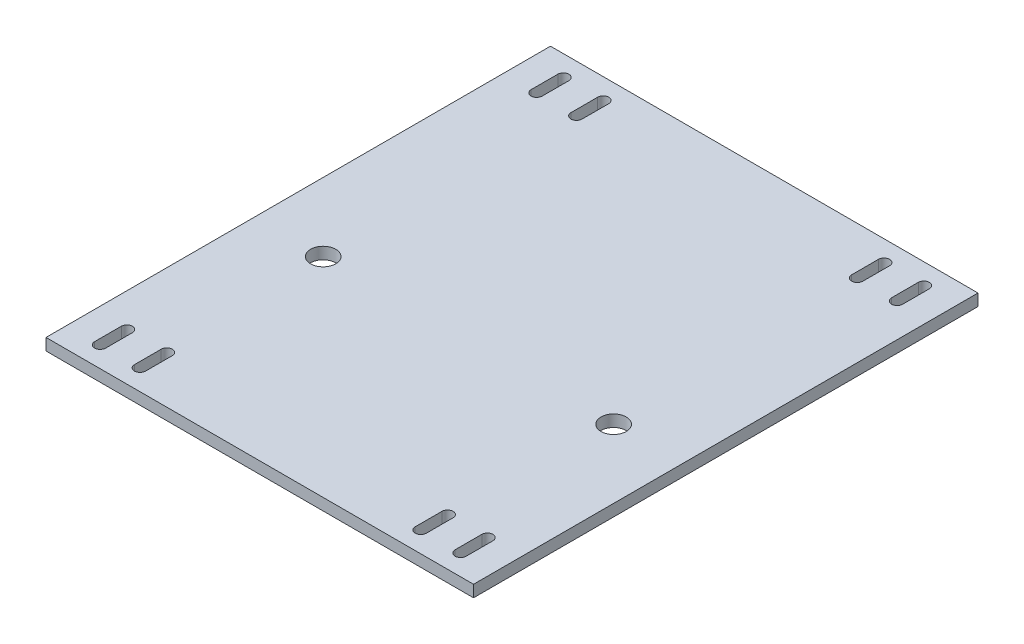
SolidWorks part; units mm, degrees
ref_plane "Front Plane" through (0, 0, 0) normal (0, 0, 1) x (1, 0, 0)
ref_plane "Top Plane" through (0, 0, 0) normal (0, 1, 0) x (1, 0, 0)
ref_plane "Right Plane" through (0, 0, 0) normal (1, 0, 0) x (0, 0, -1)
sketch "Sketch1" plane through (0, 0, 0) normal (0, 1, 0) x (1, 0, 0)
  line L1 (-76.2, -119.888) -> (76.2, -119.888)
  line L2 (-76.2, -119.888) -> (-76.2, 119.888)
  line L3 (-76.2, 119.888) -> (76.2, 119.888)
  line L4 (76.2, -119.888) -> (76.2, 119.888)
  line L5 (-76.2, -119.888) -> (76.2, 119.888) construction
  line L6 (-76.2, 119.888) -> (76.2, -119.888) construction
  point P0 (0, 0)
  dimension "D1" = 152.4
  dimension "D2" = 239.776
extrude "Boss-Extrude1" add sketch "Sketch1" along normal blind 5.588
sketch "Sketch2" plane through (0, 5.588, 0) normal (0, 1, 0) x (1, 0, 0)
  line L0 (0, 0) -> (44.9308, 9.86) construction
  line L1 (44.9308, 9.86) -> (44.9308, 0) construction
  line L2 (39.9308, -24) -> (49.9308, -24) construction
  line L3 (39.9308, -24) -> (39.9308, 24) construction
  line L4 (39.9308, 24) -> (49.9308, 24) construction
  line L5 (49.9308, -24) -> (49.9308, 24) construction
  line L6 (39.9308, -24) -> (49.9308, 24) construction
  line L7 (39.9308, 24) -> (49.9308, -24) construction
  line L8 (0, 26.208) -> (0, -26.6297) construction
  line L9 (44.9308, 0) -> (76.2, 0) construction
  line L10 (76.2, -119.888) -> (76.2, 119.888) construction
  line L11 (-33.9308, 21) -> (-55.9308, 21)
  line L12 (33.9308, -21) -> (55.9308, -21)
  line L13 (33.9308, -21) -> (33.9308, 21)
  line L14 (33.9308, 21) -> (55.9308, 21)
  line L15 (55.9308, -21) -> (55.9308, 21)
  line L16 (33.9308, -21) -> (55.9308, 21) construction
  line L17 (33.9308, 21) -> (55.9308, -21) construction
  line L18 (-55.9308, -21) -> (-55.9308, 21)
  line L19 (-33.9308, -21) -> (-55.9308, -21)
  line L20 (-33.9308, -21) -> (-33.9308, 21)
  circle A0 centre (0, 0) radius 40 construction
  circle A1 centre (44.9308, 9.86) radius 6 construction
  circle A2 centre (39.9308, 24) radius 2.25
  circle A3 centre (49.9308, 24) radius 2.25
  circle A4 centre (39.9308, -24) radius 2.25
  circle A5 centre (49.9308, -24) radius 2.25
  circle A6 centre (-49.9308, -24) radius 2.25
  circle A7 centre (-39.9308, -24) radius 2.25
  circle A8 centre (-49.9308, 24) radius 2.25
  circle A9 centre (-39.9308, 24) radius 2.25
  point P5 (44.9308, 0)
  dimension "D1" = 80
  dimension "D2" = 12
  dimension "D6" = 4.5
  dimension "D3" = 9.86
  dimension "D4" = 48
  dimension "D5" = 10
  dimension "D7" = 42
  dimension "D8" = 22
extrude "Cut-Extrude4" cut sketch "Sketch5" against normal through all
sketch "Sketch5" plane through (-207.7253, 5.588, -0.628) normal (0, 1, 0) x (0.9995, 0, 0.0329)
  circle A2 centre (230.4517, -13.7866) radius 6
  circle A3 centre (186.2997, -15.2389) radius 6
extrude "Cut-Extrude6" cut sketch "Sketch7" against normal through all
sketch "Sketch7" plane through (-338.2002, 5.588, 0) normal (0, 1, 0) x (1, 0, 0)
  line L0 (271.47, 97.3777) -> (271.47, 110.0777) construction
  line L2 (268.82, 97.3777) -> (268.82, 105.3777) construction
  line L3 (274.12, 105.3777) -> (274.12, 97.3777) construction
  line L4 (268.82, 97.3777) -> (268.82, 110.0777)
  line L5 (274.12, 97.3777) -> (274.12, 110.0777)
  arc A2 (268.82, 97.3777) -> (274.12, 97.3777) centre (271.47, 97.3777) ccw construction
  arc A3 (274.12, 105.3777) -> (268.82, 105.3777) centre (271.47, 105.3777) ccw construction
  arc A4 (268.82, 97.3777) -> (274.12, 97.3777) centre (271.47, 97.3777) ccw
  arc A5 (274.12, 110.0777) -> (268.82, 110.0777) centre (271.47, 110.0777) ccw
  point P3 (271.47, 103.7277)
  dimension "D2" = 2.65
  dimension "D1" = 8
  dimension "D3" = 12.7
mirror "Mirror1" about plane through (0, 0, 0) normal (0, 0, 1) of "Cut-Extrude6" second plane through (0, 0, 0) second plane normal (1, 0, 0)
sketch "Sketch8" plane through (-76.2, 0, 0) normal (-1, 0, 0) x (0, 0, 1)
  line L4 (-119.888, 0) -> (119.888, 0)
  line L5 (119.888, 0) -> (119.888, 5.588)
  line L6 (119.888, 5.588) -> (-119.888, 5.588)
  line L7 (-119.888, 5.588) -> (-119.888, 0)
  line L8 (-119.888, 0) -> (119.888, 0)
  line L9 (119.888, 0) -> (119.888, 5.588)
  line L10 (119.888, 5.588) -> (-119.888, 5.588)
  line L11 (-119.888, 5.588) -> (-119.888, 0)
  dimension "D1" = 0
extrude "Boss-Extrude2" add sketch "Sketch8" along normal blind 25.4
sketch "Sketch9" plane through (0, 5.588, 0) normal (0, 1, 0) x (1, 0, 0)
  line L0 (-76.2, 119.888) -> (-76.2, 0) construction
  line L1 (76.2, 119.888) -> (-101.6, 119.888) construction
  line L2 (-101.6, -119.888) -> (-101.6, 119.888) construction
  line L9 (0, 0) -> (-101.6, 0) construction
  line L12 (-69.3803, 110.0777) -> (-69.3803, 97.3777) construction
  line L13 (-64.0803, 97.3777) -> (-64.0803, 110.0777) construction
  line L14 (-69.3803, 110.0777) -> (-69.3803, 97.3777)
  line L15 (-64.0803, 97.3777) -> (-64.0803, 110.0777)
  line L16 (-88.3197, 97.3777) -> (-88.3197, 110.0777)
  line L17 (-83.0197, 110.0777) -> (-83.0197, 97.3777)
  line L18 (-88.3197, -97.3777) -> (-88.3197, -110.0777)
  line L19 (-83.0197, -110.0777) -> (-83.0197, -97.3777)
  arc A8 (-69.3803, 97.3777) -> (-64.0803, 97.3777) centre (-66.7303, 97.3777) ccw construction
  arc A9 (-64.0803, 110.0777) -> (-69.3803, 110.0777) centre (-66.7303, 110.0777) ccw construction
  arc A10 (-69.3803, 97.3777) -> (-64.0803, 97.3777) centre (-66.7303, 97.3777) ccw
  arc A11 (-64.0803, 110.0777) -> (-69.3803, 110.0777) centre (-66.7303, 110.0777) ccw
  arc A12 (-88.3197, 110.0777) -> (-83.0197, 110.0777) centre (-85.6697, 110.0777) cw
  arc A13 (-83.0197, 97.3777) -> (-88.3197, 97.3777) centre (-85.6697, 97.3777) cw
  arc A14 (-83.0197, -97.3777) -> (-88.3197, -97.3777) centre (-85.6697, -97.3777) ccw
  arc A15 (-88.3197, -110.0777) -> (-83.0197, -110.0777) centre (-85.6697, -110.0777) ccw
  dimension "D1" = 25.4
extrude "Cut-Extrude7" cut sketch "Sketch9" against normal through all
mirror "Mirror2" about plane through (0, 0, 0) normal (1, 0, 0) of "Cut-Extrude7", "Boss-Extrude2"
extrude "Cut-Extrude8" cut sketch "Sketch10" against normal through all
sketch "Sketch10" plane through (-338.2002, 5.588, 0) normal (0, 1, 0) x (1, 0, 0)
  circle A4 centre (269.1763, -20.7273) radius 6
mirror "Mirror3" about plane through (0, 0, 0) normal (1, 0, 0) of "Cut-Extrude8"
